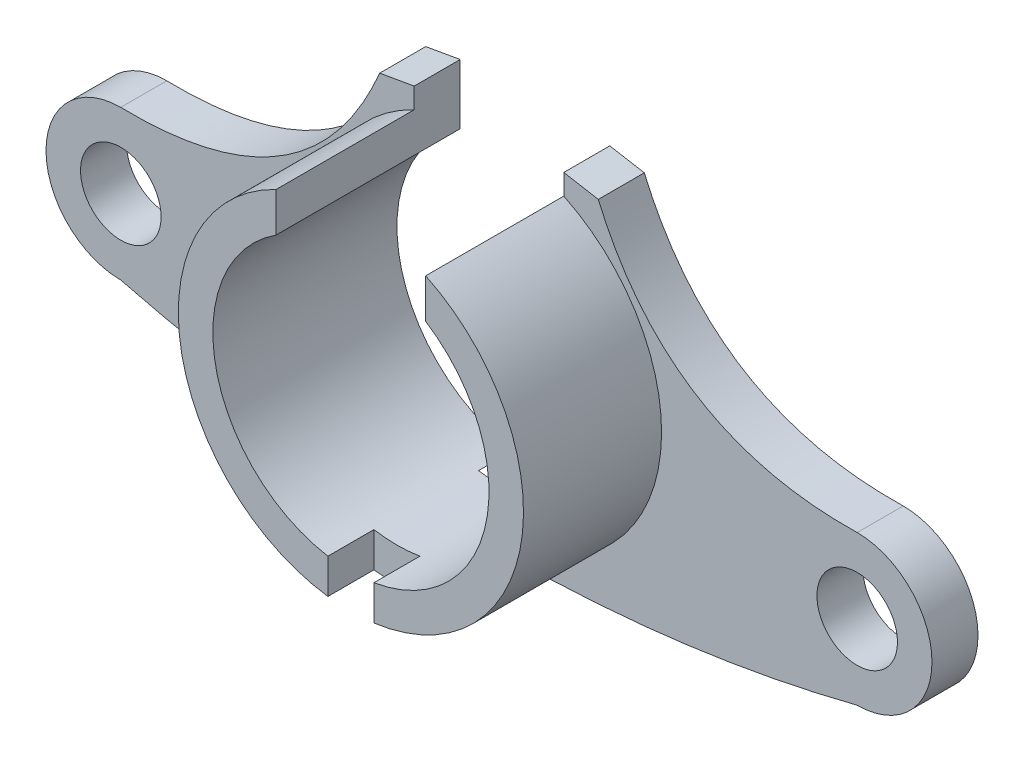
SolidWorks part; units mm, degrees
ref_plane "Front Plane" through (0, 0, 0) normal (0, 0, 1) x (1, 0, 0)
ref_plane "Top Plane" through (0, 0, 0) normal (0, 1, 0) x (1, 0, 0)
ref_plane "Right Plane" through (0, 0, 0) normal (1, 0, 0) x (0, 0, -1)
sketch "Sketch1" plane through (0, 0, 0) normal (0, 0, 1) x (1, 0, 0)
  line L0 (-24.457, 69.4319) -> (24.457, 69.4319) construction
  line L1 (0, 92) -> (0, 69.4319) construction
  line L2 (0, 77.7769) -> (23.8002, 77.7769) construction
  line L3 (-3.25, 88.8205) -> (3.25, 88.8205)
  line L4 (-3.25, 88.8205) -> (-3.25, 91.4269)
  line L5 (-3.25, 91.4269) -> (3.25, 91.4269)
  line L6 (3.25, 88.8205) -> (3.25, 91.4269)
  line L7 (-16, 81) -> (0, 81) construction
  line L8 (-8, 76.2477) -> (-8, 81) construction
  line L18 (24.457, 69.4319) -> (23.1215, 86.4007)
  line L19 (21.475, 88.2134) -> (0, 92)
  line L20 (0, 92) -> (-21.475, 88.2134)
  line L21 (-23.1215, 86.4007) -> (-24.457, 69.4319)
  line L22 (-24.5714, 68.9048) -> (-33.6515, 43.9576)
  line L23 (-33.4302, 42.1552) -> (-25.3419, 30.1639)
  line L24 (-25, 29.0455) -> (-25, -29.0455)
  line L25 (-25.3419, -30.1639) -> (-33.4302, -42.1552)
  line L26 (-33.6515, -43.9576) -> (-24.5714, -68.9048)
  line L27 (-24.457, -69.4319) -> (-23.1215, -86.4007)
  line L28 (-21.475, -88.2134) -> (0, -92)
  line L29 (0, -92) -> (21.475, -88.2134)
  line L30 (23.1215, -86.4007) -> (24.457, -69.4319)
  line L31 (24.5714, -68.9048) -> (33.6515, -43.9576)
  line L32 (33.4302, -42.1552) -> (25.3419, -30.1639)
  line L33 (25, -29.0455) -> (25, 29.0455)
  line L34 (25.3419, 30.1639) -> (33.4302, 42.1552)
  line L35 (33.6515, 43.9576) -> (24.5714, 68.9048)
  line L36 (24.457, 69.4319) -> (23.1215, 86.4007)
  line L37 (21.475, 88.2134) -> (0, 92)
  line L38 (0, 92) -> (-21.475, 88.2134)
  line L39 (-23.1215, 86.4007) -> (-24.457, 69.4319)
  line L40 (-24.5714, 68.9048) -> (-33.6515, 43.9576)
  line L41 (-33.4302, 42.1552) -> (-25.3419, 30.1639)
  line L42 (-25, 29.0455) -> (-25, -29.0455)
  line L43 (-25.3419, -30.1639) -> (-33.4302, -42.1552)
  line L44 (-33.6515, -43.9576) -> (-24.5714, -68.9048)
  line L45 (-24.457, -69.4319) -> (-23.1215, -86.4007)
  line L46 (-21.475, -88.2134) -> (0, -92)
  line L47 (0, -92) -> (21.475, -88.2134)
  line L48 (23.1215, -86.4007) -> (24.457, -69.4319)
  line L49 (24.5714, -68.9048) -> (33.6515, -43.9576)
  line L50 (33.4302, -42.1552) -> (25.3419, -30.1639)
  line L51 (25, -29.0455) -> (25, 29.0455)
  line L52 (25.3419, 30.1639) -> (33.4302, 42.1552)
  line L53 (33.6515, 43.9576) -> (24.5714, 68.9048)
  circle A0 centre (-16, 81) radius 1.5 construction
  circle A1 centre (-16, 81) radius 1.5
  circle A2 centre (16, 81) radius 1.5 construction
  circle A3 centre (16, 81) radius 1.5
  circle A4 centre (-16, 81) radius 1.75
  circle A5 centre (16, 81) radius 1.75
  circle A6 centre (0, 83.7769) radius 6
  circle A7 centre (-16, 81) radius 3.25
  circle A8 centre (16, 81) radius 3.25
  arc A16 (24.457, 69.4319) -> (24.5714, 68.9048) centre (26.4508, 69.5889) ccw
  arc A17 (23.1215, 86.4007) -> (21.475, 88.2134) centre (21.1277, 86.2438) ccw
  arc A18 (-21.475, 88.2134) -> (-23.1215, 86.4007) centre (-21.1277, 86.2438) ccw
  arc A19 (-24.5714, 68.9048) -> (-24.457, 69.4319) centre (-26.4508, 69.5889) ccw
  arc A20 (-33.6515, 43.9576) -> (-33.4302, 42.1552) centre (-31.7721, 43.2736) ccw
  arc A21 (-25, 29.0455) -> (-25.3419, 30.1639) centre (-27, 29.0455) ccw
  arc A22 (-25.3419, -30.1639) -> (-25, -29.0455) centre (-27, -29.0455) ccw
  arc A23 (-33.4302, -42.1552) -> (-33.6515, -43.9576) centre (-31.7721, -43.2736) ccw
  arc A24 (-24.457, -69.4319) -> (-24.5714, -68.9048) centre (-26.4508, -69.5889) ccw
  arc A25 (-23.1215, -86.4007) -> (-21.475, -88.2134) centre (-21.1277, -86.2438) ccw
  arc A26 (21.475, -88.2134) -> (23.1215, -86.4007) centre (21.1277, -86.2438) ccw
  arc A27 (24.5714, -68.9048) -> (24.457, -69.4319) centre (26.4508, -69.5889) ccw
  arc A28 (33.6515, -43.9576) -> (33.4302, -42.1552) centre (31.7721, -43.2736) ccw
  arc A29 (25, -29.0455) -> (25.3419, -30.1639) centre (27, -29.0455) ccw
  arc A30 (25.3419, 30.1639) -> (25, 29.0455) centre (27, 29.0455) ccw
  arc A31 (33.4302, 42.1552) -> (33.6515, 43.9576) centre (31.7721, 43.2736) ccw
  arc A32 (24.457, 69.4319) -> (24.5714, 68.9048) centre (26.4508, 69.5889) ccw
  arc A33 (23.1215, 86.4007) -> (21.475, 88.2134) centre (21.1277, 86.2438) ccw
  arc A34 (-21.475, 88.2134) -> (-23.1215, 86.4007) centre (-21.1277, 86.2438) ccw
  arc A35 (-24.5714, 68.9048) -> (-24.457, 69.4319) centre (-26.4508, 69.5889) ccw
  arc A36 (-33.6515, 43.9576) -> (-33.4302, 42.1552) centre (-31.7721, 43.2736) ccw
  arc A37 (-25, 29.0455) -> (-25.3419, 30.1639) centre (-27, 29.0455) ccw
  arc A38 (-25.3419, -30.1639) -> (-25, -29.0455) centre (-27, -29.0455) ccw
  arc A39 (-33.4302, -42.1552) -> (-33.6515, -43.9576) centre (-31.7721, -43.2736) ccw
  arc A40 (-24.457, -69.4319) -> (-24.5714, -68.9048) centre (-26.4508, -69.5889) ccw
  arc A41 (-23.1215, -86.4007) -> (-21.475, -88.2134) centre (-21.1277, -86.2438) ccw
  arc A42 (21.475, -88.2134) -> (23.1215, -86.4007) centre (21.1277, -86.2438) ccw
  arc A43 (24.5714, -68.9048) -> (24.457, -69.4319) centre (26.4508, -69.5889) ccw
  arc A44 (33.6515, -43.9576) -> (33.4302, -42.1552) centre (31.7721, -43.2736) ccw
  arc A45 (25, -29.0455) -> (25.3419, -30.1639) centre (27, -29.0455) ccw
  arc A46 (25.3419, 30.1639) -> (25, 29.0455) centre (27, 29.0455) ccw
  arc A47 (33.4302, 42.1552) -> (33.6515, 43.9576) centre (31.7721, 43.2736) ccw
  spline S0 degree 2 poles (-16, 77.75) (-8.1248, 75.7473) (0, 75.7769) knots 0 0 0 1 1 1
  spline S1 degree 2 poles (16, 77.75) (8.1248, 75.7473) (0, 75.7769) knots 0 0 0 1 1 1
  spline S2 degree 2 poles (-16, 84.25) (-7.7794, 84.0631) (-4.75, 91.1624) knots 0 0 0 1 1 1
  spline S3 degree 2 poles (16, 84.25) (7.7794, 84.0631) (4.75, 91.1624) knots 0 0 0 1 1 1
  dimension "D2" = 3.5
  dimension "D3" = 12
  dimension "D4" = 1.5
  dimension "D5" = 6.5
  dimension "D6" = 13.65
  dimension "D7" = 2
  dimension "D8" = 4.7523
  dimension "D9" = 5.6521
  dimension "D10" = 1.5
  dimension "D1" = 0
extrude "Boss-Extrude1" add sketch "Sketch1" along normal blind 2 contours S2 A7 A4 | A8 S3 L37 L6 A6 L4 L38 S2 A7 S0 S1 | A8 S3 A5
sketch "Sketch2" plane through (0, 0, 2) normal (0, 0, 1) x (1, 0, 0)
  line L4 (4.75, 91.1624) -> (3.25, 91.4269)
  line L5 (3.25, 91.4269) -> (3.25, 88.8205)
  line L6 (-3.25, 88.8205) -> (-3.25, 91.4269)
  line L7 (-3.25, 91.4269) -> (-4.75, 91.1624)
  line L8 (4.75, 91.1624) -> (3.25, 91.4269)
  line L9 (3.25, 91.4269) -> (3.25, 88.8205)
  line L10 (-3.25, 88.8205) -> (-3.25, 91.4269)
  line L11 (-3.25, 91.4269) -> (-4.75, 91.1624)
  circle A0 centre (0, 83.7769) radius 6
  arc A1 (-3.25, 88.8205) -> (3.25, 88.8205) centre (0, 83.7769) ccw construction
  circle A2 centre (0, 83.7769) radius 7.5
  arc A5 (-16, 84.25) -> (-16, 77.75) centre (-16, 81) ccw
  arc A6 (16, 77.75) -> (16, 84.25) centre (16, 81) ccw
  arc A7 (-3.25, 88.8205) -> (3.25, 88.8205) centre (0, 83.7769) ccw
  arc A8 (-16, 84.25) -> (-16, 77.75) centre (-16, 81) ccw
  arc A9 (16, 77.75) -> (16, 84.25) centre (16, 81) ccw
  arc A10 (-3.25, 88.8205) -> (3.25, 88.8205) centre (0, 83.7769) ccw
  parabola Q4 (-4.75, 91.1624) -> (-16, 84.25) focus (-11.3394, 90.1995) apex (-8.5255, 86.25)
  parabola Q5 (-16, 77.75) -> (0, 75.7769) focus (-4.1631, 107.7468) apex (-8.0312, 76.2516)
  parabola Q6 (0, 75.7769) -> (16, 77.75) focus (4.1631, 107.7468) apex (8.0312, 76.2516)
  parabola Q7 (16, 84.25) -> (4.75, 91.1624) focus (11.3394, 90.1995) apex (8.5255, 86.25)
  parabola Q8 (-4.75, 91.1624) -> (-16, 84.25) focus (-11.3394, 90.1995) apex (-8.5255, 86.25)
  parabola Q9 (-16, 77.75) -> (0, 75.7769) focus (-4.1631, 107.7468) apex (-8.0312, 76.2516)
  parabola Q10 (0, 75.7769) -> (16, 77.75) focus (4.1631, 107.7468) apex (8.0312, 76.2516)
  parabola Q11 (16, 84.25) -> (4.75, 91.1624) focus (11.3394, 90.1995) apex (8.5255, 86.25)
  arc M20 (3.25, 88.8205) -> (-3.25, 88.8205) centre (0, 83.7769) cw
  line M21 (-3.25, 88.8205) -> (-3.25, 91.4269)
  dimension "D2" = 1.5
  dimension "D1" = 0
extrude "Boss-Extrude2" add sketch "Sketch2" along normal blind 6 contours A2 L9 M21 M20
sketch "Sketch4" plane through (0, 0, 8) normal (0, 0, 1) x (1, 0, 0)
  line L0 (0, 83.7769) -> (0, 75.7769) construction
  line L1 (0, 77.8609) -> (0, 76.2769) construction
  line L2 (-1, 77.8609) -> (1, 77.8609)
  line L3 (-1, 77.8609) -> (-1, 76.2769)
  line L4 (-1, 76.2769) -> (1, 76.2769)
  line L5 (1, 77.8609) -> (1, 76.2769)
  arc A0 (-3.25, 88.8205) -> (3.25, 88.8205) centre (0, 83.7769) ccw construction
  arc A2 (-3.25, 90.5362) -> (3.25, 90.5362) centre (0, 83.7769) ccw construction
  dimension "D1" = 2
extrude "Cut-Extrude1" cut sketch "Sketch4" against normal blind 2
sketch "Sketch5" plane through (0, 0, 0) normal (0, 0, -1) x (-1, 0, 0)
  line L0 (0, 83.7769) -> (0, 70.3883) construction
  line L1 (0, 77.7769) -> (16.1056, 77.7769) construction
  line L2 (0, 78.0243) -> (17.0426, 78.0243) construction
  circle A0 centre (0, 75.2743) radius 2.75
  arc A2 (-3.25, 88.8205) -> (3.25, 88.8205) centre (0, 83.7769) ccw construction
  parabola Q7 (16, 77.75) -> (0, 75.7769) focus (4.1631, 107.7468) apex (8.0312, 76.2516) construction
  parabola Q24 (16, 77.75) -> (0, 75.7769) focus (4.1631, 107.7468) apex (8.0312, 76.2516) construction
  dimension "D1" = 5.5
  dimension "D2" = 0.2474
extrude "Cut-Extrude3" cut sketch "Sketch5" against normal blind 1.5
